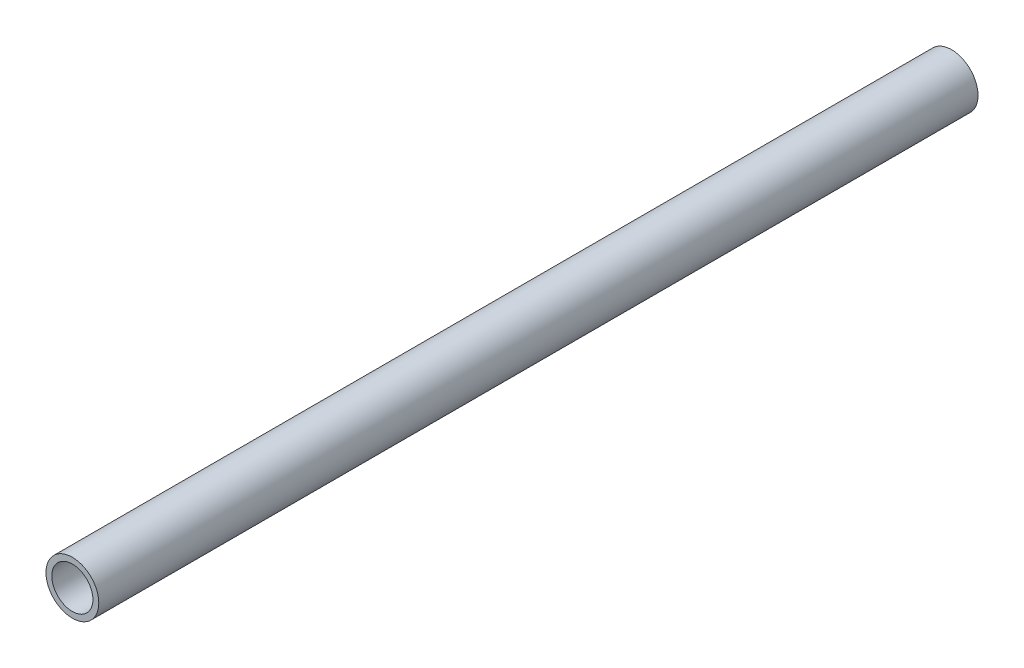
SolidWorks part; units mm, degrees
ref_plane "Front Plane" through (0, 0, 0) normal (0, 0, 1) x (1, 0, 0)
ref_plane "Top Plane" through (0, 0, 0) normal (0, 1, 0) x (1, 0, 0)
ref_plane "Right Plane" through (0, 0, 0) normal (1, 0, 0) x (0, 0, -1)
sketch "Sketch1" plane through (0, 0, 0) normal (0, 0, 1) x (1, 0, 0)
  circle A0 centre (0, 0) radius 9
  circle A1 centre (0, 0) radius 7
  dimension "D1" = 14
  dimension "D2" = 18
extrude "Boss-Extrude1" add sketch "Sketch1" along normal blind 299.527
